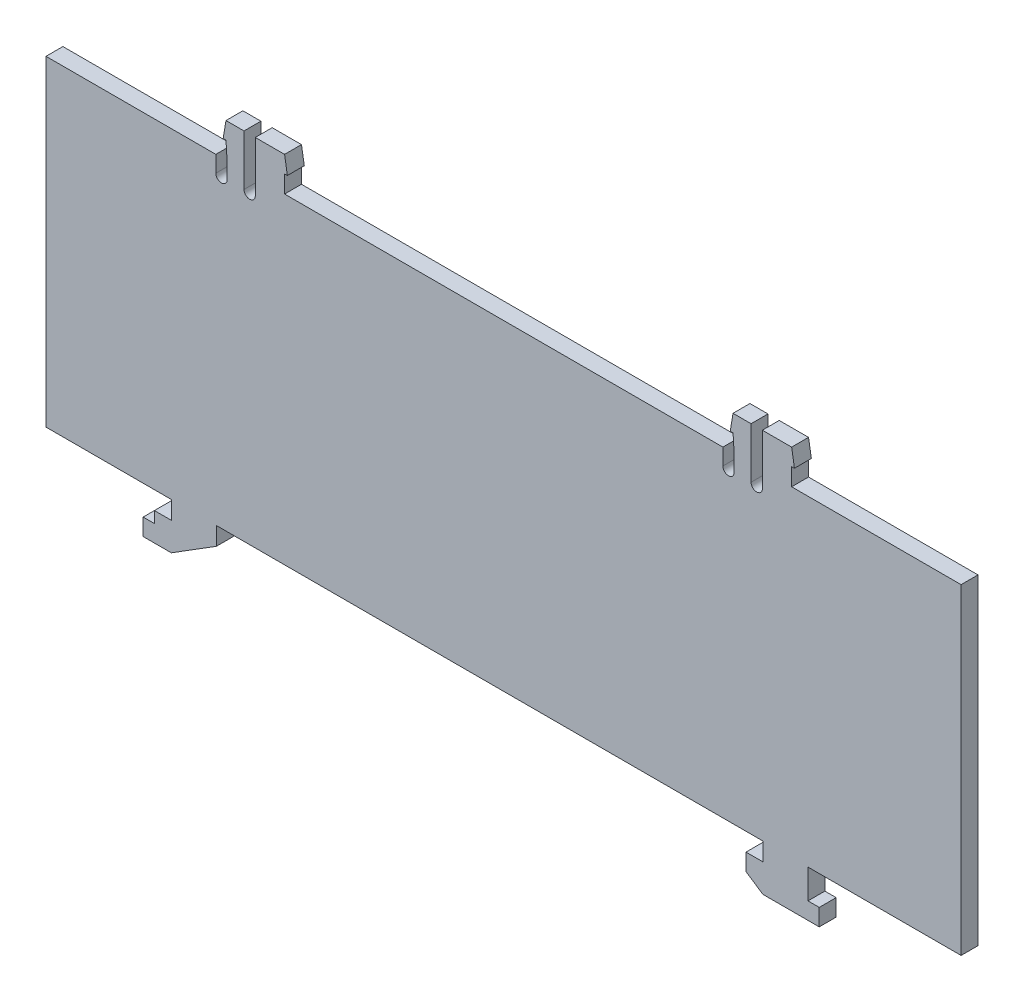
SolidWorks part; units mm, degrees
ref_plane "Front Plane" through (0, 0, 0) normal (0, 0, 1) x (1, 0, 0)
ref_plane "Top Plane" through (0, 0, 0) normal (0, 1, 0) x (1, 0, 0)
ref_plane "Right Plane" through (0, 0, 0) normal (1, 0, 0) x (0, 0, -1)
sketch "Sketch1" plane through (0, 0, 0) normal (0, 0, 1) x (1, 0, 0)
  line L0 (133, 60) -> (-133, 60) construction
  line L1 (80.1785, 3) -> (-82.2432, 3)
  line L2 (80.1785, 3) -> (80.1785, 60)
  line L3 (80.1785, 60) -> (-82.2432, 60)
  line L4 (-82.2432, 3) -> (-82.2432, 60)
  line L5 (133, 3) -> (-133, 3) construction
extrude "Boss-Extrude1" add sketch "Sketch1" along normal up to vertex (3 mm away)
sketch "Sketch2" plane through (0, 0, 0) normal (0, 0, -1) x (-1, 0, 0)
  line L0 (60, 0) -> (60, 3) construction
  line L2 (52, 3) -> (60, 3)
  line L3 (82.2432, 3) -> (-80.1785, 3) construction
  line L4 (60, 3) -> (60, -0.2)
  line L5 (60, -0.2) -> (63, -0.2)
  line L6 (63, -0.2) -> (63, -2.2)
  line L7 (-53, -2.2) -> (-55, -2.2)
  line L8 (52, -0.2) -> (52, 3)
  line L9 (-53, 3) -> (-53, -2.2)
  line L10 (65, -5.2) -> (60, -5.2)
  line L11 (-42, -3.2) -> (-42, -0.2)
  line L12 (-42, -0.2) -> (-45, -0.2)
  line L13 (-45, -0.2) -> (-45, 3)
  line L14 (-45, 3) -> (-53, 3)
  line L15 (0, 0) -> (85.2405, 0) construction
  line L16 (-45, 0) -> (-45, 3) construction
  line L17 (63, -2.2) -> (65, -2.2)
  line L18 (65, -2.2) -> (65, -5.2)
  line L19 (60, -5.2) -> (52, -0.2)
  line L20 (-55, -2.2) -> (-55, -5.2)
  line L21 (-55, -5.2) -> (-45, -5.2)
  line L22 (-45, -5.2) -> (-42, -3.2)
  dimension "D1" = 2
  dimension "D2" = 0.2
  dimension "D3" = 8
  dimension "D4" = 3
  dimension "D5" = 2
  dimension "D6" = 3
  dimension "D7" = 8
  dimension "D8" = 2
  dimension "D9" = 2
extrude "bottom hooks" add sketch "Sketch2" against normal up to surface (3 mm away) up to face at (-1.0323, 31.5, 3)
sketch "Sketch3" plane through (0, 0, 0) normal (0, 0, -1) x (-1, 0, 0)
  line L0 (-80.1785, 60) -> (82.2432, 60) construction
  line L1 (0, 0) -> (0, 60) construction
  line B0 (-39.7, 63.1) -> (-39.9, 60)
  line B1 (-37.9, 60) -> (-35.9, 60)
  line B2 (-50.1, 63.1) -> (-50.1, 60)
  line B3 (-50.1, 60) -> (-52.1, 60)
  line B4 (-42.9, 57.1) -> (-42.9, 66.1)
  line B5 (-50.1, 66.1) -> (-44.9, 66.1)
  line B6 (-44.9, 57.1) -> (-44.9, 68.9) construction
  line B7 (-39.9, 60) -> (-39.9, 57.1)
  line B8 (-37.9, 57.1) -> (-37.9, 60)
  line B9 (-39.7, 63.1) -> (-39.2, 63.1)
  line B10 (-39.2, 63.1) -> (-39.7, 66.1)
  line B11 (-42.9, 66.1) -> (-39.7, 66.1)
  line B12 (-44.9, 66.1) -> (-44.9, 57.1)
  line B13 (-50.1, 63.1) -> (-50.6, 63.1)
  line B14 (-50.6, 63.1) -> (-50.1, 66.1)
  arc B15 (-44.9, 57.1) -> (-42.9, 57.1) centre (-43.9, 57.1) ccw
  arc B16 (-39.9, 57.1) -> (-37.9, 57.1) centre (-38.9, 57.1) ccw
  line B17 (-52.1, 63) -> (-35.9, 63) construction
  line B18 (-43.9, 57.1) -> (-38.9, 57.1) construction
  line B19 (-35.9, 63) -> (-35.9, 60) construction
  line B20 (-50.1, 60) -> (-37.9, 60) construction
  line B21 (-52.1, 60) -> (-52.1, 53)
  line B22 (-52.1, 53) -> (-35.9, 53)
  line B23 (-35.9, 53) -> (-35.9, 60)
  line B24 (50.3, 63.1) -> (50.1, 60)
  line B25 (52.1, 60) -> (54.1, 60)
  line B26 (39.9, 63.1) -> (39.9, 60)
  line B27 (39.9, 60) -> (37.9, 60)
  line B28 (47.1, 57.1) -> (47.1, 66.1)
  line B29 (39.9, 66.1) -> (45.1, 66.1)
  line B30 (45.1, 57.1) -> (45.1, 68.9) construction
  line B31 (50.1, 60) -> (50.1, 57.1)
  line B32 (52.1, 57.1) -> (52.1, 60)
  line B33 (50.3, 63.1) -> (50.8, 63.1)
  line B34 (50.8, 63.1) -> (50.3, 66.1)
  line B35 (47.1, 66.1) -> (50.3, 66.1)
  line B36 (45.1, 66.1) -> (45.1, 57.1)
  line B37 (39.9, 63.1) -> (39.4, 63.1)
  line B38 (39.4, 63.1) -> (39.9, 66.1)
  arc B39 (45.1, 57.1) -> (47.1, 57.1) centre (46.1, 57.1) ccw
  arc B40 (50.1, 57.1) -> (52.1, 57.1) centre (51.1, 57.1) ccw
  line B41 (37.9, 63) -> (54.1, 63) construction
  line B42 (50.3, 63.1) -> (50.3, 66.1) construction
  line B43 (46.1, 57.1) -> (51.1, 57.1) construction
  line B44 (54.1, 63) -> (54.1, 60) construction
  line B45 (39.9, 60) -> (52.1, 60) construction
  line B46 (37.9, 60) -> (37.9, 53)
  line B47 (37.9, 53) -> (54.1, 53)
  line B48 (54.1, 53) -> (54.1, 60)
sketch_block_instance "external-tooth-tab-1"
sketch_block "external-tooth-tab" parameters "D1"=1, "D2"=6, "D3"=3, "D4"=3.1, "D5"=10.2, "D6"=0.2, "D7"=0.5, "D8"=3, "D9"=4.3072, "D10"=5, "D11"=0.5
sketch_block_instance "external-tooth-tab-2"
extrude "top tabs" add sketch "Sketch3" against normal up to surface (3 mm away) up to face at (-8.2882, 4.7364, 3)
sketch "Sketch4" plane through (0, 0, 0) normal (0, 0, -1) x (-1, 0, 0)
  line L0 (47.1, 57.1) -> (47.1, 66.1) construction
  line L1 (45.1, 66.1) -> (45.1, 57.1) construction
  line L2 (50.1, 60) -> (50.1, 57.1) construction
  line L3 (52.1, 57.1) -> (52.1, 60) construction
  line L4 (-44.9, 66.1) -> (-44.9, 57.1) construction
  line L5 (-42.9, 57.1) -> (-42.9, 66.1) construction
  line L6 (-39.9, 60) -> (-39.9, 57.1) construction
  line L7 (-37.9, 57.1) -> (-37.9, 60) construction
  line L8 (47.1, 57.1) -> (47.1, 66.1)
  line L9 (45.1, 66.1) -> (45.1, 57.1)
  line L10 (50.1, 60) -> (50.1, 57.1)
  line L11 (52.1, 57.1) -> (52.1, 60)
  line L12 (-44.9, 66.1) -> (-44.9, 57.1)
  line L13 (-42.9, 57.1) -> (-42.9, 66.1)
  line L14 (-39.9, 60) -> (-39.9, 57.1)
  line L15 (-37.9, 57.1) -> (-37.9, 60)
  line L16 (-44.9, 66.1) -> (-42.9, 66.1)
  line L17 (-39.9, 60) -> (-37.9, 60)
  line L18 (45.1, 66.1) -> (47.1, 66.1)
  line L19 (50.1, 60) -> (52.1, 60)
  arc A0 (45.1, 57.1) -> (47.1, 57.1) centre (46.1, 57.1) ccw construction
  arc A1 (50.1, 57.1) -> (52.1, 57.1) centre (51.1, 57.1) ccw construction
  arc A2 (-44.9, 57.1) -> (-42.9, 57.1) centre (-43.9, 57.1) ccw construction
  arc A3 (-39.9, 57.1) -> (-37.9, 57.1) centre (-38.9, 57.1) ccw construction
  arc A4 (45.1, 57.1) -> (47.1, 57.1) centre (46.1, 57.1) ccw
  arc A5 (50.1, 57.1) -> (52.1, 57.1) centre (51.1, 57.1) ccw
  arc A6 (-44.9, 57.1) -> (-42.9, 57.1) centre (-43.9, 57.1) ccw
  arc A7 (-39.9, 57.1) -> (-37.9, 57.1) centre (-38.9, 57.1) ccw
extrude "top tab relief" cut sketch "Sketch4" against normal up to next
